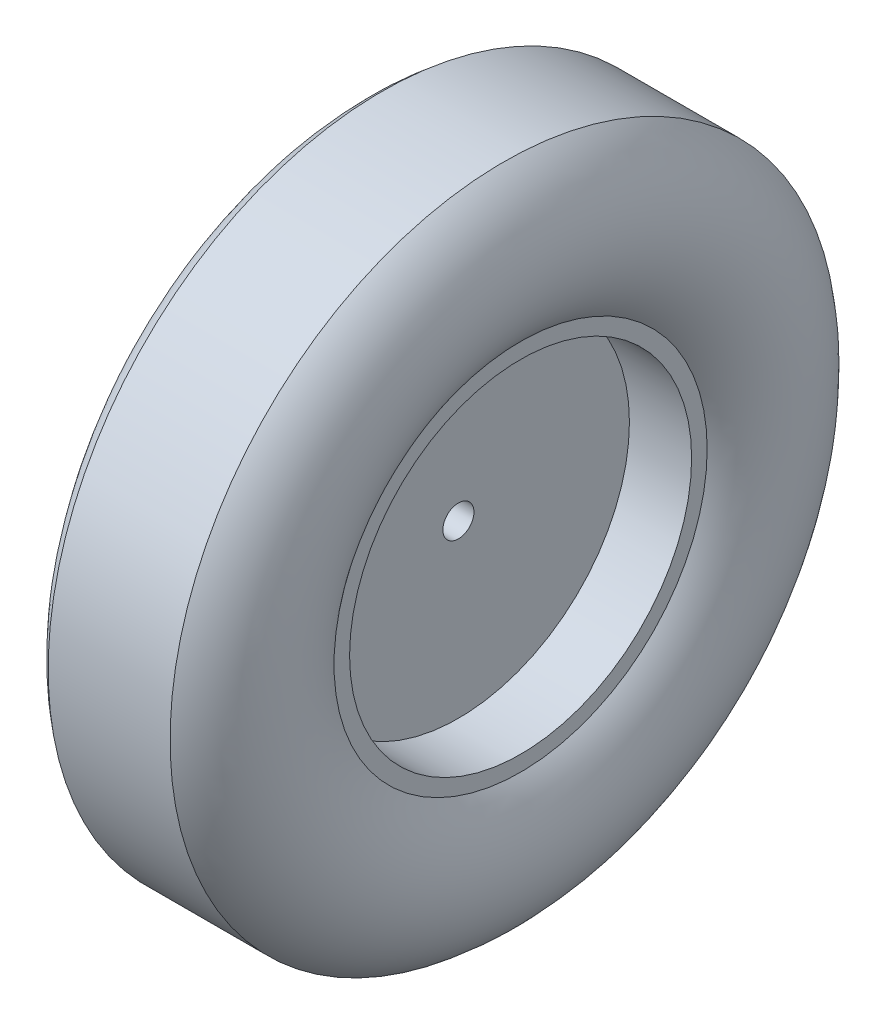
SolidWorks part; units mm, degrees
ref_plane "Front Plane" through (0, 0, 0) normal (0, 0, 1) x (1, 0, 0)
ref_plane "Top Plane" through (0, 0, 0) normal (0, 1, 0) x (1, 0, 0)
ref_plane "Right Plane" through (0, 0, 0) normal (1, 0, 0) x (0, 0, -1)
sketch "Sketch3" plane through (0, 0, 0) normal (0, 0, 1) x (1, 0, 0)
  line L0 (12.7, 0) -> (-12.7, 0)
  line L1 (0, 0) -> (0, 12.7)
  line L2 (12.7, 12.7) -> (-12.7, 12.7)
  line L3 (-12.7, 12.7) -> (-12.7, 139.7)
  line L4 (12.7, 12.7) -> (12.7, 139.7)
  line L5 (-12.7, 139.7) -> (-63.5, 139.7)
  line L6 (-63.5, 139.7) -> (-63.5, 152.4)
  line L7 (12.7, 139.7) -> (63.5, 139.7)
  line L8 (63.5, 139.7) -> (63.5, 152.4)
  line L9 (63.5, 152.4) -> (-63.5, 152.4)
  line L10 (49.7956, 272.622) -> (-49.7956, 272.622)
  arc A0 (63.5, 152.4) -> (-63.5, 152.4) centre (0, 206.0536) ccw
  point P4 (0, 0)
  point P10 (0, 12.7)
  point P19 (0, 272.622)
  dimension "D1" = 25.4
  dimension "D2" = 127
  dimension "D3" = 127
  dimension "D4" = 50.8
  dimension "D5" = 12.7
  dimension "D6" = 50.8
  dimension "D7" = 12.7
revolve "Revolve1" add sketch "Sketch3" angle 360 about L0
